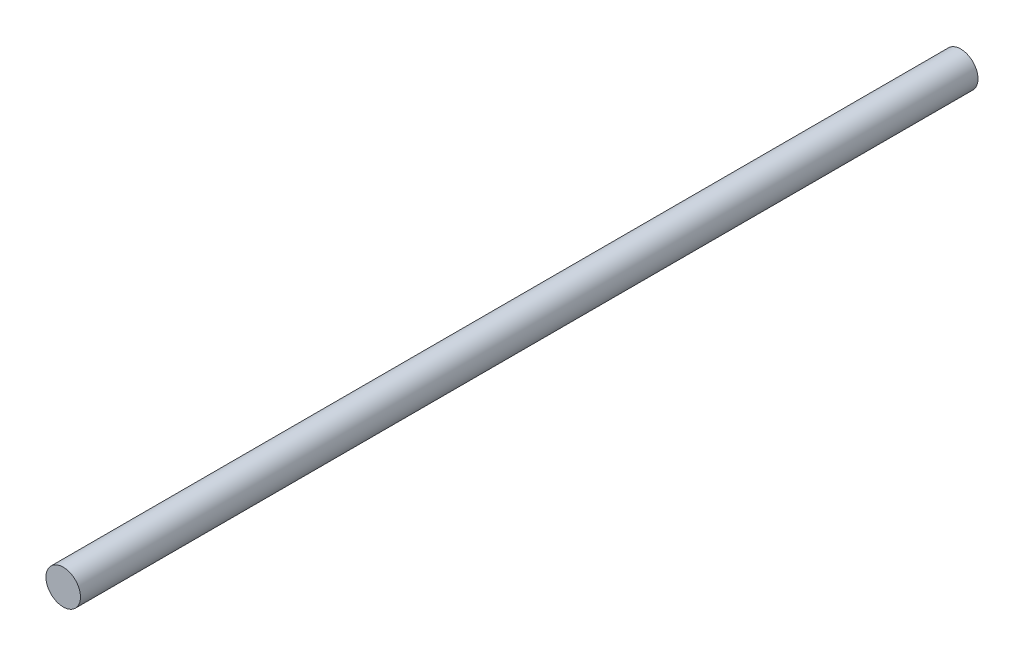
SolidWorks part; units mm, degrees
ref_plane "Front Plane" through (0, 0, 0) normal (0, 0, 1) x (1, 0, 0)
ref_plane "Top Plane" through (0, 0, 0) normal (0, 1, 0) x (1, 0, 0)
ref_plane "Right Plane" through (0, 0, 0) normal (1, 0, 0) x (0, 0, -1)
sketch "Sketch1" plane through (0, 0, 0) normal (0, 0, 1) x (1, 0, 0)
  circle A0 centre (0, 0) radius 5
  dimension "D1" = 10
extrude "Boss-Extrude1" add sketch "Sketch1" along normal blind 260
